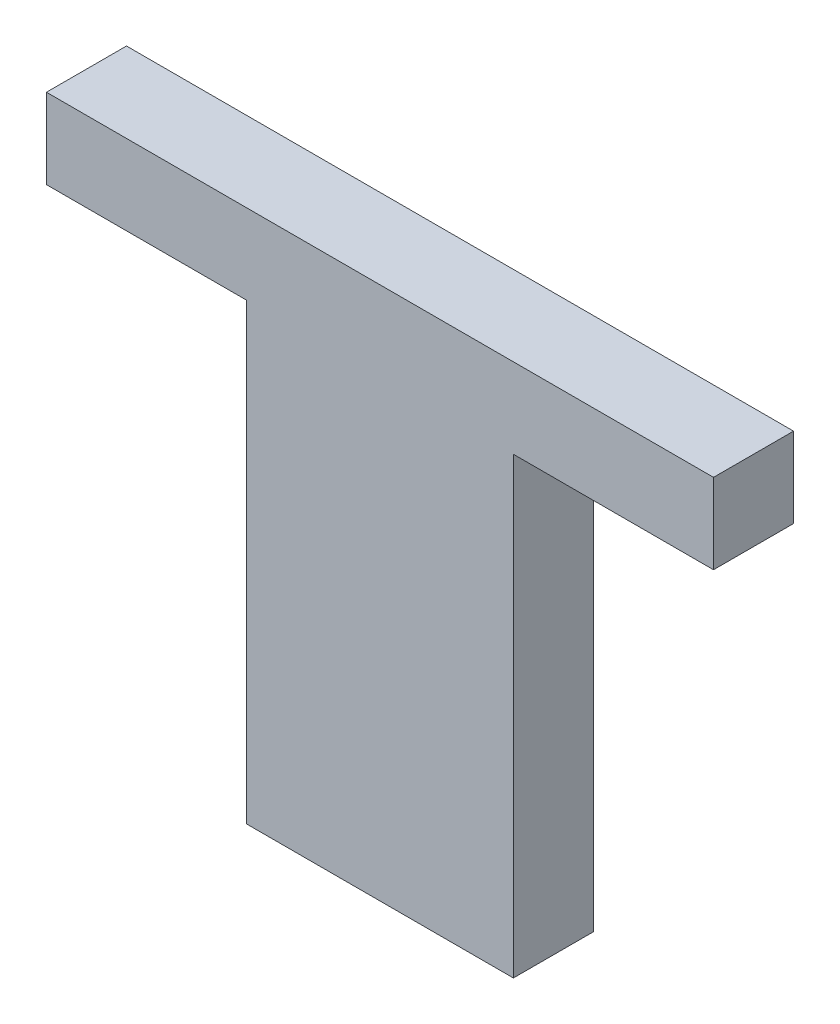
SolidWorks part; units mm, degrees
ref_plane "Plan de face" through (0, 0, 0) normal (0, 0, 1) x (1, 0, 0)
ref_plane "Plan de dessus" through (0, 0, 0) normal (0, 1, 0) x (1, 0, 0)
ref_plane "Plan de droite" through (0, 0, 0) normal (1, 0, 0) x (0, 0, -1)
sketch "Esquisse1" plane through (0, 0, 0) normal (0, 0, 1) x (1, 0, 0)
  line L1 (0, 0) -> (50, 0)
  line L2 (0, 0) -> (0, 40)
  line L3 (0, 40) -> (50, 40)
  line L4 (50, 0) -> (50, 40)
  dimension "D1" = 50
  dimension "D2" = 40
extrude "Boss.-Extru.1" add sketch "Esquisse1" along normal blind 6
sketch "Esquisse2" plane through (0, 0, 6) normal (0, 0, 1) x (1, 0, 0)
  line L0 (50, 40) -> (0, 40) construction
  line L1 (0, 0) -> (15, 0)
  line L2 (0, 0) -> (0, 34)
  line L3 (0, 34) -> (15, 34)
  line L4 (15, 0) -> (15, 34)
  line L5 (50, 0) -> (35, 0)
  line L6 (50, 0) -> (50, 34)
  line L7 (50, 34) -> (35, 34)
  line L8 (35, 0) -> (35, 34)
  dimension "D1" = 20
  dimension "D2" = 15
  dimension "D3" = 15
  dimension "D4" = 6
  dimension "D5" = 6
extrude "Enlèv. mat.-Extru.1" cut sketch "Esquisse2" against normal blind 6
